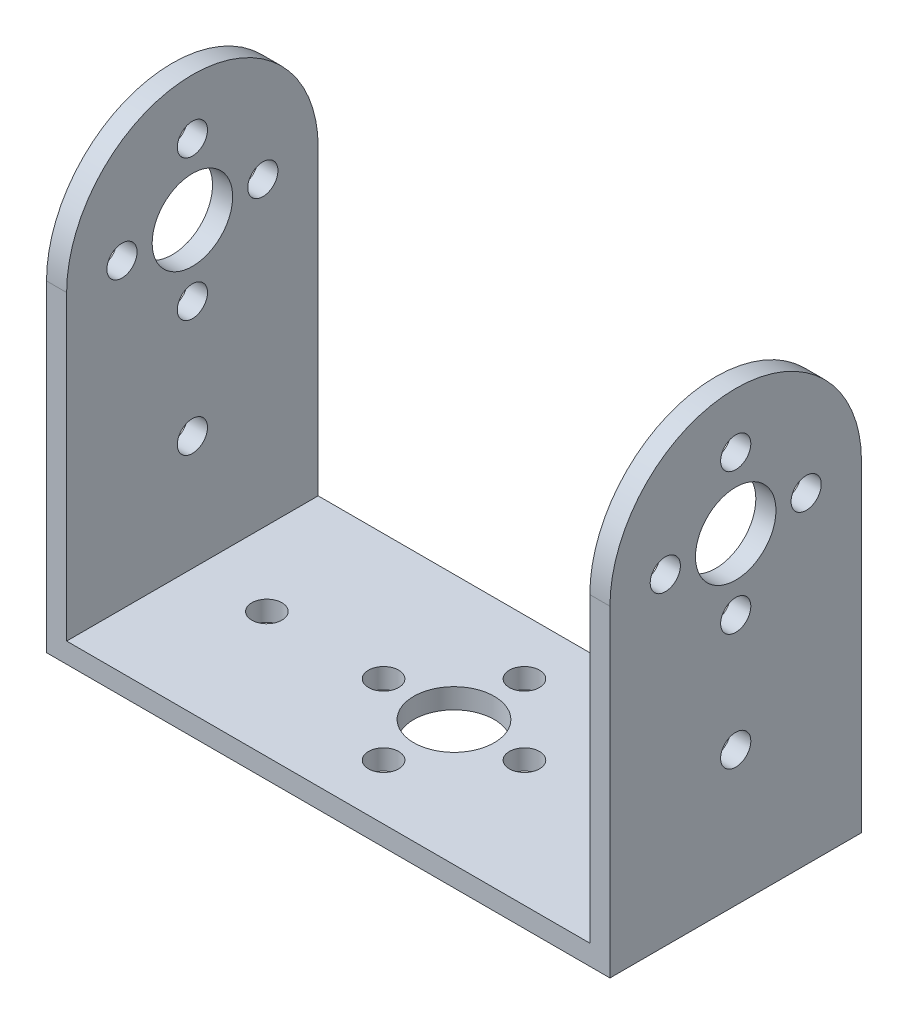
SolidWorks part; units mm, degrees
ref_plane "前视基准面" through (0, 0, 0) normal (0, 0, 1) x (1, 0, 0)
ref_plane "上视基准面" through (0, 0, 0) normal (0, 1, 0) x (1, 0, 0)
ref_plane "右视基准面" through (0, 0, 0) normal (1, 0, 0) x (0, 0, -1)
sketch "草图1" plane through (0, 0, 0) normal (0, 1, 0) x (1, 0, 0)
  line L1 (-20.3457, 13.2314) -> (35.6543, 13.2314)
  line L2 (-20.3457, 13.2314) -> (-20.3457, -11.7686)
  line L3 (-20.3457, -11.7686) -> (35.6543, -11.7686)
  line L4 (35.6543, 13.2314) -> (35.6543, -11.7686)
  dimension "D1" = 25
  dimension "D2" = 56
extrude "凸台-拉伸1" add sketch "草图1" along normal blind 2
sketch "草图2" plane through (0, 2, 0) normal (0, 1, 0) x (1, 0, 0)
  line L0 (7.6543, 13.2314) -> (7.6543, -11.7686) construction
  line L1 (35.6543, 13.2314) -> (-20.3457, 13.2314) construction
  line L2 (-20.3457, -11.7686) -> (35.6543, -11.7686) construction
  line L3 (-20.3457, 0.7314) -> (35.6543, 0.7314) construction
  line L4 (-20.3457, 13.2314) -> (-20.3457, -11.7686) construction
  line L5 (35.6543, -11.7686) -> (35.6543, 13.2314) construction
  circle A0 centre (7.6543, 0.7314) radius 4
  circle A1 centre (7.6543, 0.7314) radius 7 construction
  circle A2 centre (7.6543, 7.7314) radius 1.5
  circle A3 centre (14.6543, 0.7314) radius 1.5
  circle A4 centre (7.6543, -6.2686) radius 1.5
  circle A5 centre (0.6543, 0.7314) radius 1.5
  circle A6 centre (-10.9457, 0.7314) radius 1.5
  circle A7 centre (26.2543, 0.7314) radius 1.5
  point P26 (7.6543, 0.7314)
  dimension "D1" = 4
  dimension "D2" = 37.2
extrude "切除-拉伸1" cut sketch "草图2" against normal through all
sketch "草图3" plane through (-20.3457, 0, 0) normal (-1, 0, 0) x (0, 0, 1)
  line L1 (-13.2314, 2) -> (11.7686, 2)
  line L2 (-13.2314, 2) -> (-13.2314, 32)
  line L4 (11.7686, 2) -> (11.7686, 32)
  arc A0 (11.7686, 32) -> (-13.2314, 32) centre (-0.7314, 32) ccw
  dimension "D1" = 30
  dimension "D2" = 25
extrude "凸台-拉伸2" add sketch "草图3" against normal blind 2
sketch "草图4" plane through (-20.3457, 0, 0) normal (-1, 0, 0) x (0, 0, 1)
  line L0 (-13.2314, 32) -> (11.7686, 32) construction
  line L1 (-0.7314, 32) -> (-0.7314, 44.5) construction
  circle A1 centre (-0.7314, 32) radius 4
  circle A2 centre (-0.7314, 39) radius 1.5
  circle A3 centre (6.2686, 32) radius 1.5
  circle A4 centre (-0.7314, 25) radius 1.5
  circle A5 centre (-7.7314, 32) radius 1.5
  circle A6 centre (-0.7314, 13.4) radius 1.5
  point P21 (-0.7314, 32)
  dimension "D1" = 7
  dimension "D3" = 18.6
  dimension "D2" = 4
extrude "切除-拉伸2" cut sketch "草图4" against normal up to next
ref_plane "基准面1" through (7.6543, 0, 0) normal (-1, 0, 0) x (0, 0, 1)
mirror "镜向1" about plane through (7.6543, 0, 0) normal (-1, 0, 0) of "切除-拉伸2", "凸台-拉伸2"
